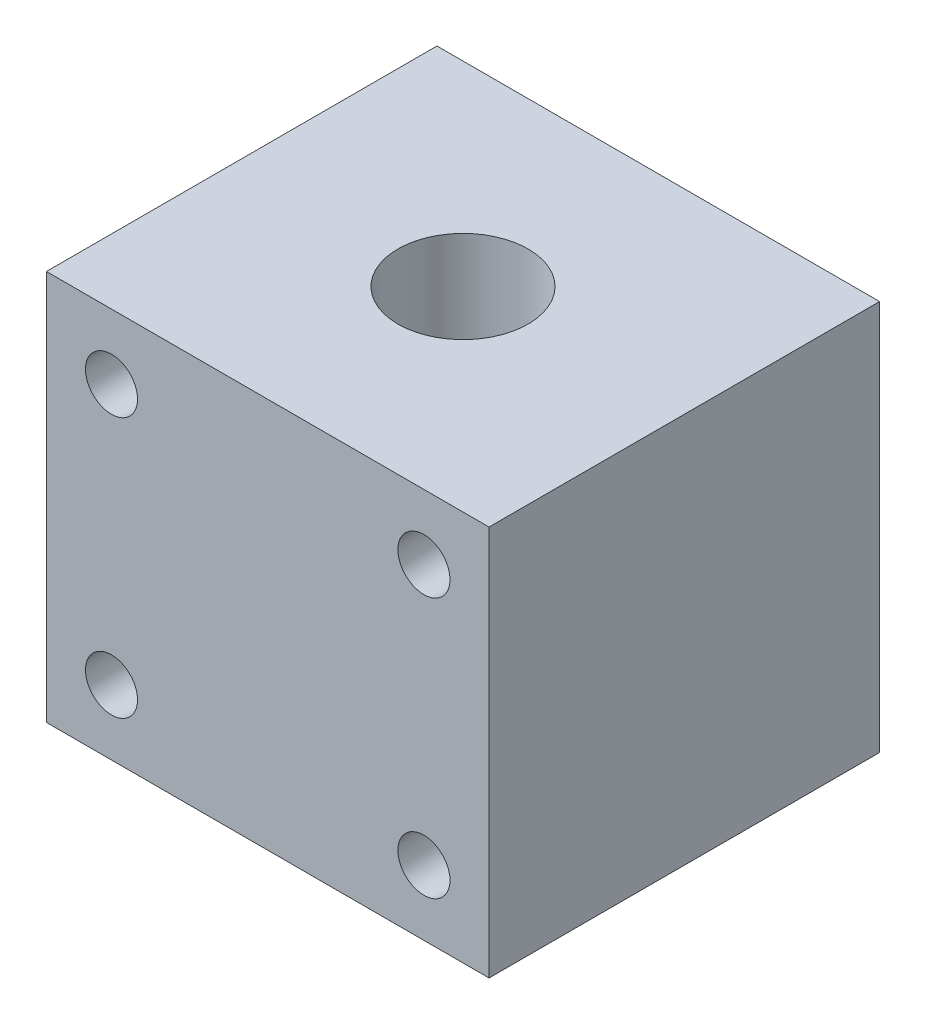
SolidWorks part; units mm, degrees
ref_plane "Front Plane" through (0, 0, 0) normal (0, 0, 1) x (1, 0, 0)
ref_plane "Top Plane" through (0, 0, 0) normal (0, 1, 0) x (1, 0, 0)
ref_plane "Right Plane" through (0, 0, 0) normal (1, 0, 0) x (0, 0, -1)
sketch "Sketch1" plane through (0, 0, 0) normal (0, 1, 0) x (1, 0, 0)
  line L0 (0, -15) -> (34, -15) construction
  line L1 (0, 0) -> (34, 0)
  line L2 (0, 0) -> (0, -30)
  line L3 (0, -30) -> (34, -30)
  line L4 (34, 0) -> (34, -30)
  line L5 (17, 0) -> (17, -30) construction
  circle A0 centre (17, -15) radius 5
  point P11 (0, 0)
  point P14 (14.0072, -15)
  point P15 (14.0072, -15)
  point P16 (17, -15)
  dimension "D3" = 10
  dimension "D1" = 34
  dimension "D2" = 30
extrude "Boss-Extrude1" add sketch "Sketch1" along normal blind 30
sketch "Sketch2" plane through (0, 0, 0) normal (0, 0, -1) x (-1, 0, 0)
  line L0 (-17, 30) -> (-17, 0) construction
  line L1 (-34, 30) -> (0, 30) construction
  line L2 (-34, 0) -> (0, 0) construction
  line L3 (-34, 15) -> (0, 15) construction
  line L4 (-34, 30) -> (-34, 0) construction
  line L5 (0, 30) -> (0, 0) construction
  circle A0 centre (-29, 25) radius 2
  circle A1 centre (-5, 25) radius 2
  circle A2 centre (-5, 5) radius 2
  circle A3 centre (-29, 5) radius 2
  point P22 (-33.5766, 30)
  point P23 (-26.3854, 30)
  dimension "D3" = 4
  dimension "D1" = 5
  dimension "D2" = 5
extrude "Cut-Extrude1" cut sketch "Sketch2" against normal through all both and the other way through all
